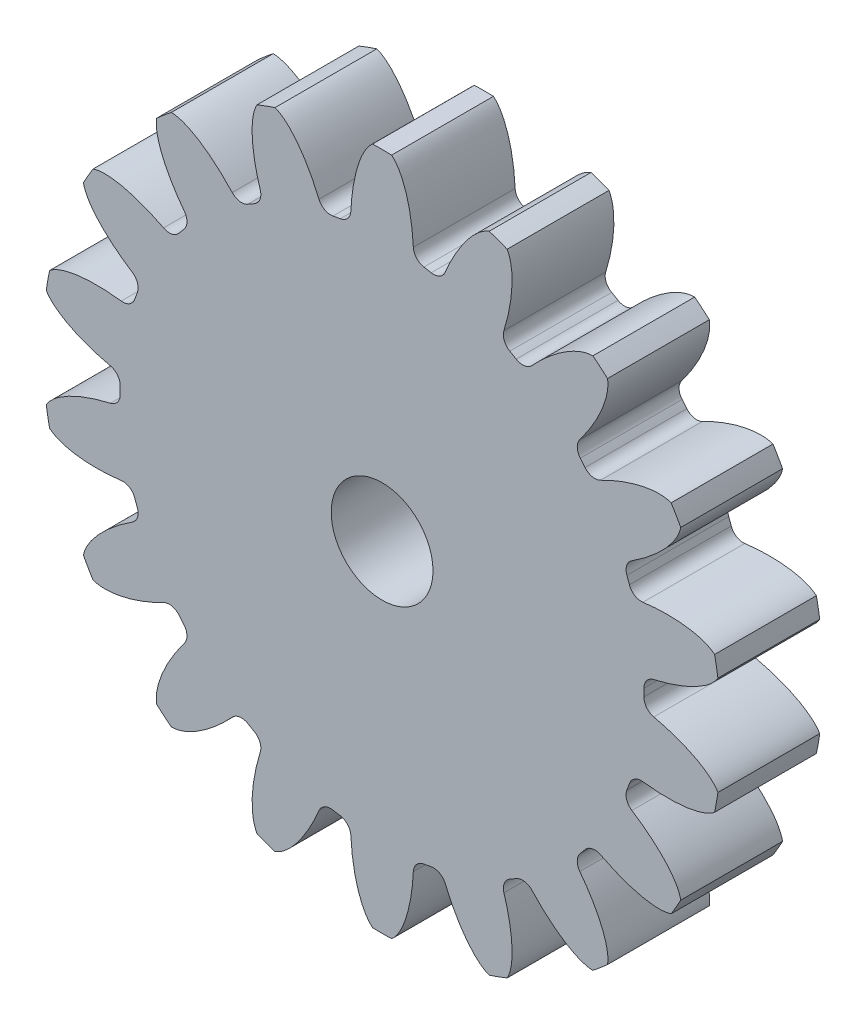
SolidWorks part; units mm, degrees
ref_plane "Front Plane" through (0, 0, 0) normal (0, 0, 1) x (1, 0, 0)
ref_plane "Top Plane" through (0, 0, 0) normal (0, 1, 0) x (1, 0, 0)
ref_plane "Right Plane" through (0, 0, 0) normal (1, 0, 0) x (0, 0, -1)
sketch "Sketch1" plane through (0, 0, 0) normal (0, 0, 1) x (1, 0, 0)
  circle A4 centre (0, 0) radius 1.5 construction
  circle A8 centre (0, 0) radius 1.286
  circle A9 centre (0, 0) radius 0.25
  dimension "D1" = 3
  dimension "D2" = 0.214
  dimension "D3" = 0.5
extrude "Boss-Extrude1" add sketch "Sketch1" along normal blind 0.5
sketch "Sketch3" plane through (0, 0, 0) normal (0, 0, 1) x (1, 0, 0)
  line L0 (0, 0) -> (0, 1.667) construction
  arc A0 (0.047, 1.6663) -> (-0.047, 1.6663) centre (0, 0) ccw
  circle A1 centre (0, 0) radius 1.286 construction
  circle A2 centre (0, 0) radius 1.286 construction
  circle A3 centre (0, 0) radius 1.5 construction
  arc A4 (0.1546, 1.2767) -> (-0.1546, 1.2767) centre (0, 0) ccw
  ellipse E0 centre (0, 1.2767) end of major axis (0, 0.8676) minor radius 0.1546 (-0.047, 1.6663) -> (-0.1546, 1.2767) ccw
  ellipse E1 centre (0, 1.2767) end of major axis (0, 0.8676) minor radius 0.1546 (0.1546, 1.2767) -> (0.047, 1.6663) ccw
  point P7 (-0.1309, 1.4943)
  point P13 (0.1309, 1.4943)
  point P14 (-0.047, 1.6663)
  point P15 (0.047, 1.6663)
  point P16 (0, 0)
  point P17 (0, 0)
  point P18 (0, 0)
  point P19 (0, 0)
  point P22 (0, 0)
  point P23 (0, 0)
  point P24 (0, 0)
  point P27 (0, 0)
  point P34 (0, 0)
  dimension "D1" = 0.381
  dimension "D2" = 0.094
  dimension "D3" = 0.2618
extrude "Boss-Extrude2" add sketch "Sketch3" along normal up to surface (0.5 mm away) up to face at (1.286, 0, 0.5)
fillet "Fillet4" radius 0.062 2 edges at (0.1546, 1.2767, 0.25) (-0.1546, 1.2767, 0.25)
pattern_circular "CirPattern8" count 18 over 360 about axis through (0, 0, 0.5) along (0, 0, 1) of "Fillet4", "Boss-Extrude2"
